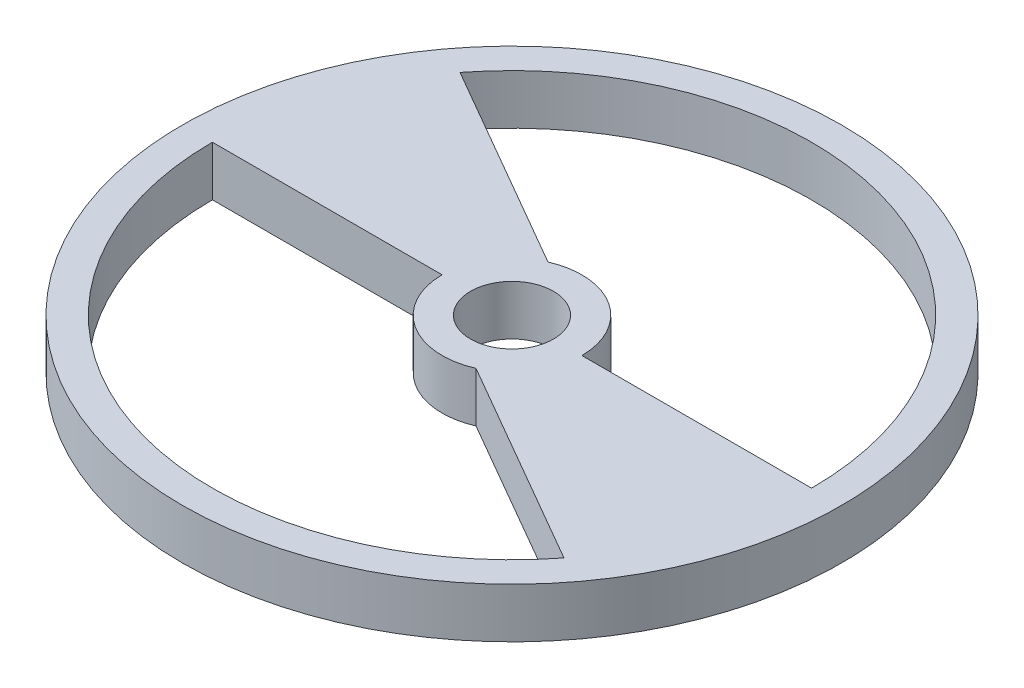
SolidWorks part; units mm, degrees
ref_plane "Front Plane" through (0, 0, 0) normal (0, 0, 1) x (1, 0, 0)
ref_plane "Top Plane" through (0, 0, 0) normal (0, 1, 0) x (1, 0, 0)
ref_plane "Right Plane" through (0, 0, 0) normal (1, 0, 0) x (0, 0, -1)
sketch "Sketch1" plane through (0, 0, 0) normal (0, 1, 0) x (1, 0, 0)
  line L0 (-3.5, 0) -> (-15, 0)
  line L1 (-11.828, 9.2249) -> (-1.4035, 3.2063)
  line L2 (3.5, 0) -> (15, 0)
  line L3 (1.4035, -3.2063) -> (11.828, -9.2249)
  circle A0 centre (0, 0) radius 16.5
  arc A1 (-15, 0) -> (11.828, -9.2249) centre (0, 0) ccw
  circle A2 centre (0, 0) radius 2.075
  arc A3 (3.5, 0) -> (-1.4035, 3.2063) centre (0, 0) ccw
  arc A4 (15, 0) -> (-11.828, 9.2249) centre (0, 0) ccw
  arc A5 (-3.5, 0) -> (1.4035, -3.2063) centre (0, 0) ccw
  dimension "D2" = 30
  dimension "D3" = 4.15
  dimension "D4" = 7
  dimension "D5" = 30
  dimension "D6" = 30
  dimension "D1" = 1.5
extrude "Boss-Extrude1" add sketch "Sketch1" along normal blind 2.5
equation "\"D6@Sketch1\"=\"D5@Sketch1\""
